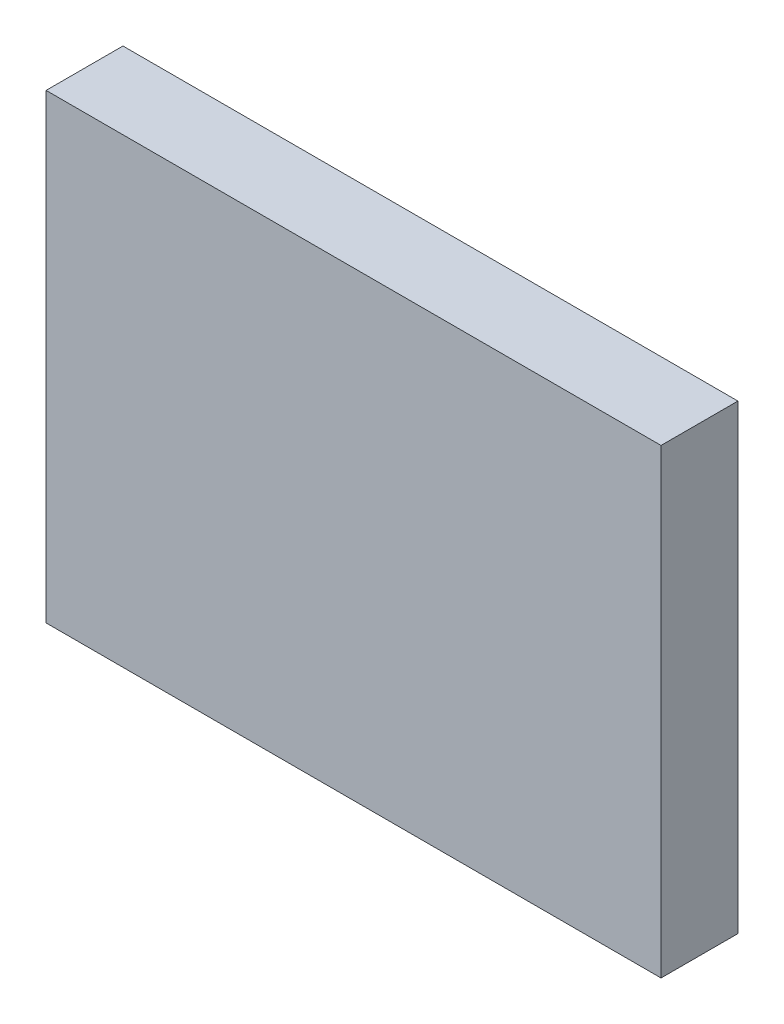
SolidWorks part; units mm, degrees
ref_plane "Plan de face" through (0, 0, 0) normal (0, 0, 1) x (1, 0, 0)
ref_plane "Plan de dessus" through (0, 0, 0) normal (0, 1, 0) x (1, 0, 0)
ref_plane "Plan de droite" through (0, 0, 0) normal (1, 0, 0) x (0, 0, -1)
sketch "Esquisse1" plane through (0, 0, 0) normal (0, 0, 1) x (1, 0, 0)
  line L1 (-50.8, -38.1) -> (50.8, -38.1)
  line L2 (-50.8, -38.1) -> (-50.8, 38.1)
  line L3 (-50.8, 38.1) -> (50.8, 38.1)
  line L4 (50.8, -38.1) -> (50.8, 38.1)
  line L5 (-50.8, -38.1) -> (50.8, 38.1) construction
  line L6 (-50.8, 38.1) -> (50.8, -38.1) construction
  point P0 (0, 0)
  dimension "D1" = 101.6
  dimension "D2" = 76.2
extrude "Boss.-Extru.1" add sketch "Esquisse1" along normal blind 12.7
